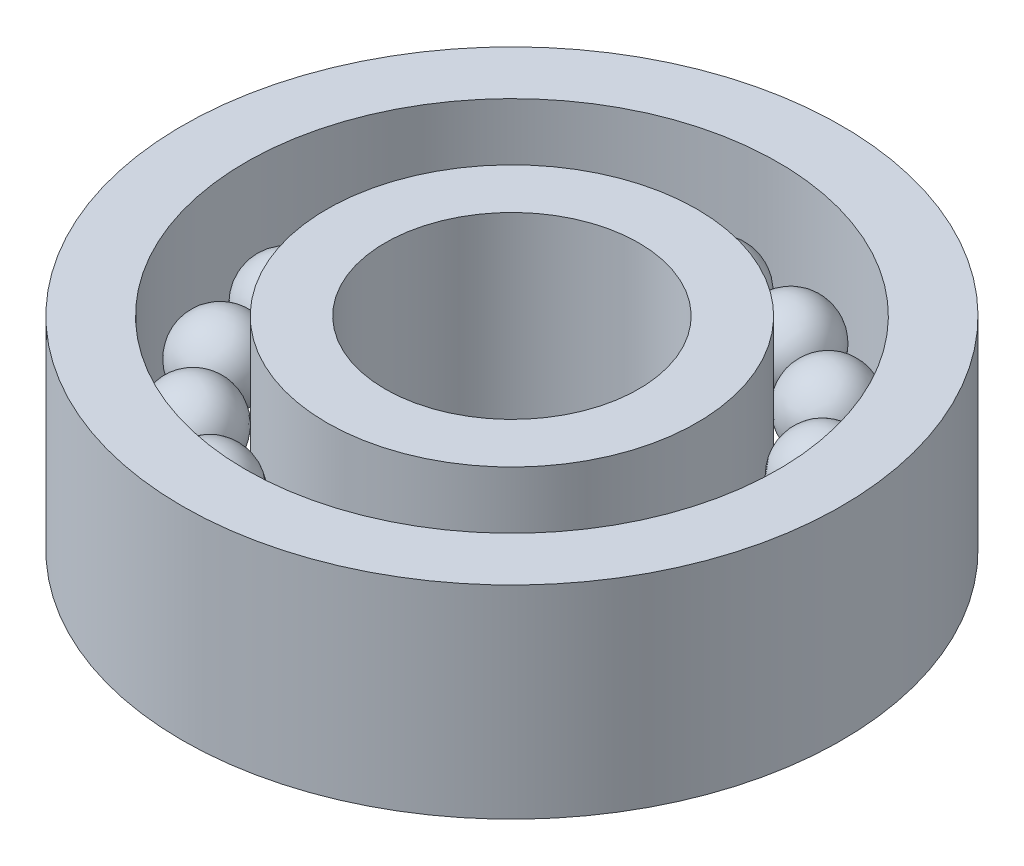
SolidWorks part; units mm, degrees
ref_plane "前视基准面" through (0, 0, 0) normal (0, 0, 1) x (1, 0, 0)
ref_plane "上视基准面" through (0, 0, 0) normal (0, 1, 0) x (1, 0, 0)
ref_plane "右视基准面" through (0, 0, 0) normal (1, 0, 0) x (0, 0, -1)
sketch "草图1" plane through (0, 0, 0) normal (0, 1, 0) x (1, 0, 0)
  circle A0 centre (0, 0) radius 2.5
  circle A1 centre (0, 0) radius 6.5
  dimension "D1" = 5
  dimension "D2" = 13
extrude "凸台-拉伸1" add sketch "草图1" along normal mid plane 4 contours A0 | A1
sketch "草图2" plane through (0, 2, 0) normal (0, 1, 0) x (1, 0, 0)
  circle A0 centre (0, 0) radius 3.65
  circle A1 centre (0, 0) radius 5.25
  dimension "D1" = 7.3
  dimension "D2" = 10.5
extrude "切除-拉伸2" cut sketch "草图2" against normal through all contours A0 | A1
sketch "草图4" plane through (0, 0, 0) normal (0, 1, 0) x (1, 0, 0)
  line L0 (-4.45, 2.2189) -> (-4.45, -2.3863) construction
  line L1 (-4.45, 0.8) -> (-4.45, -0.8)
  arc A0 (-4.45, -0.8) -> (-4.45, 0.8) centre (-4.45, 0) ccw
  dimension "D2" = 1.6
  dimension "D1" = 4.45
revolve "旋转5" add sketch "草图4" angle 360 about L0
sketch "草图5" plane through (0, 0, 0) normal (0, 0, 1) x (1, 0, 0)
  line L0 (0, 3.7203) -> (0, -3.7462) construction
pattern_circular "阵列(圆周)4" count 17 over 360 about axis through (0, 0, 0) along (0, 1, 0) of bodies 110
